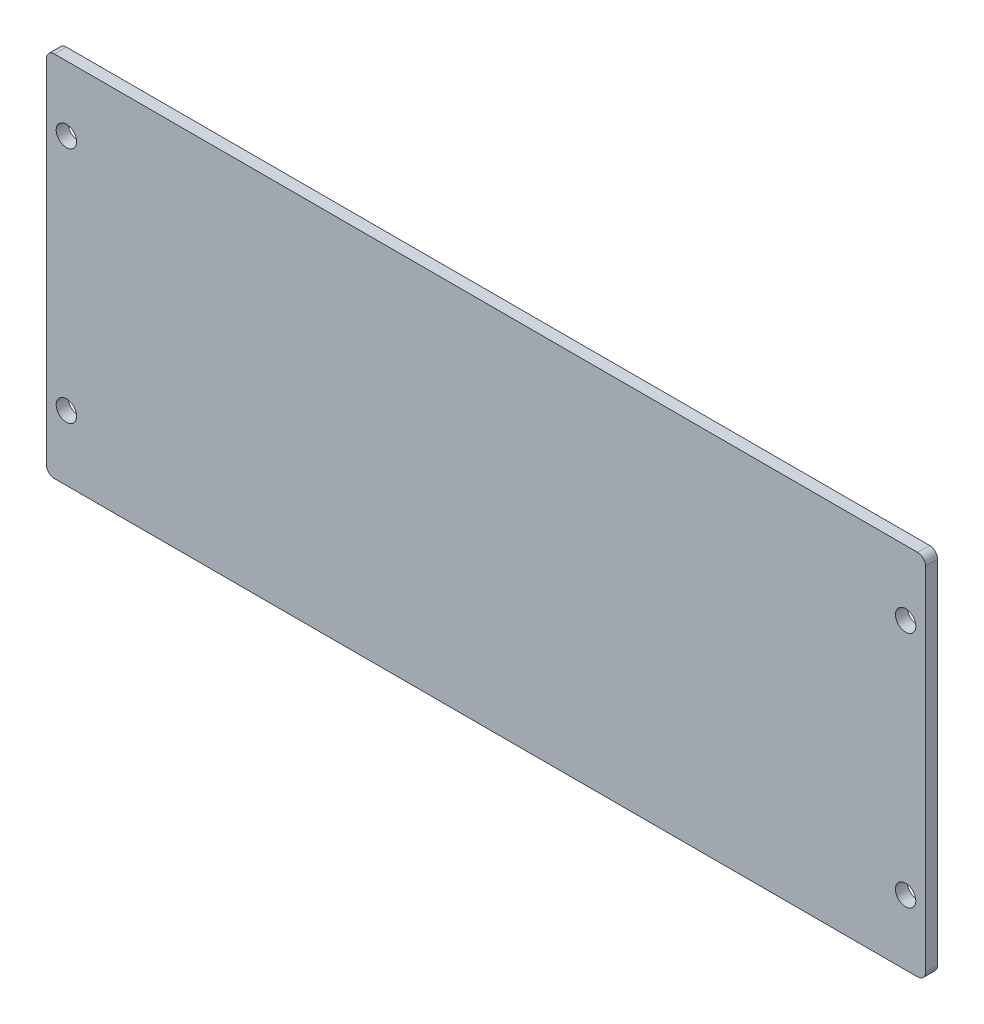
SolidWorks part; units mm, degrees
ref_plane "Front Plane" through (0, 0, 0) normal (0, 0, 1) x (1, 0, 0)
ref_plane "Top Plane" through (0, 0, 0) normal (0, 1, 0) x (1, 0, 0)
ref_plane "Right Plane" through (0, 0, 0) normal (1, 0, 0) x (0, 0, -1)
sketch "Sketch1" plane through (0, 0, 0) normal (0, 0, 1) x (1, 0, 0)
  line L0 (-100, 96) -> (100, 96)
  line L16 (110, 96) -> (100, 96)
  line L20 (-100, 96) -> (-110, 96)
  line L21 (-110, 96) -> (-110, 4)
  line L22 (-110, 4) -> (110, 4)
  line L23 (110, 4) -> (110, 96)
  circle A4 centre (105, 20.2454) radius 2.55
  circle A5 centre (105, 79.7546) radius 2.55
  circle A6 centre (-105, 20.2454) radius 2.55
  circle A7 centre (-105, 79.7546) radius 2.55
extrude "Boss-Extrude1" add sketch "Sketch1" along normal blind 3
fillet "Fillet1" radius 2 4 edges at (-110, 4, 1.5) (-110, 96, 1.5) (110, 4, 1.5) (110, 96, 1.5)
